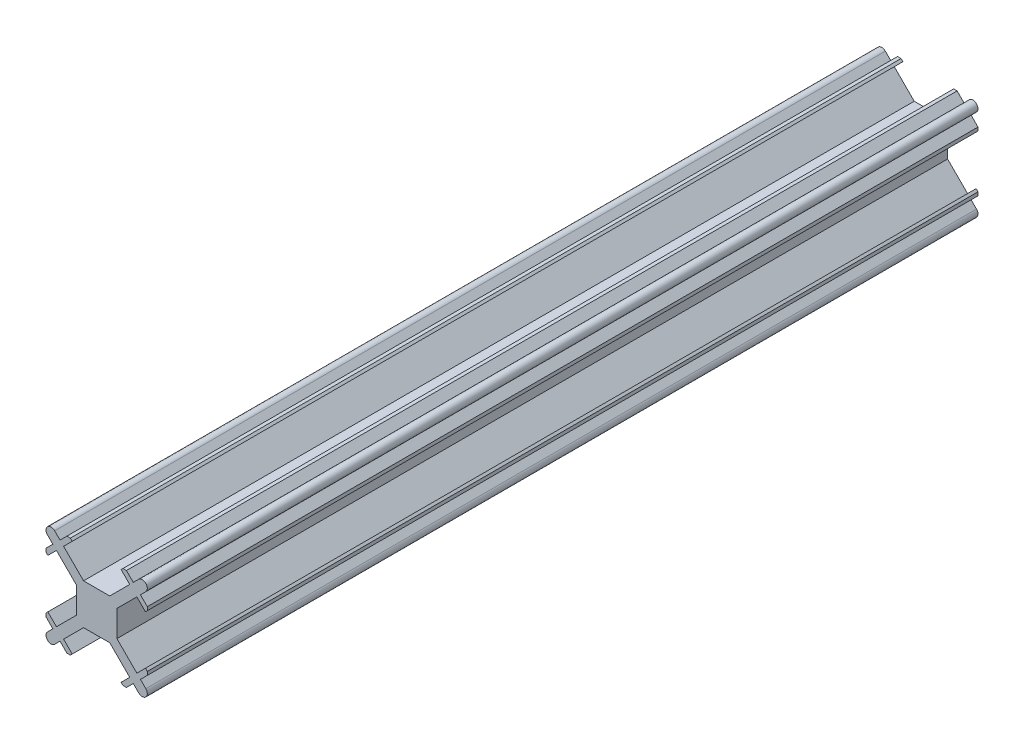
SolidWorks part; units mm, degrees
ref_plane "Front Plane" through (0, 0, 0) normal (0, 0, 1) x (1, 0, 0)
ref_plane "Top Plane" through (0, 0, 0) normal (0, 1, 0) x (1, 0, 0)
ref_plane "Right Plane" through (0, 0, 0) normal (1, 0, 0) x (0, 0, -1)
sketch "Sketch1" plane through (0, 0, 0) normal (0, 0, 1) x (1, 0, 0)
  line L0 (-5, -5) -> (5, 5) construction
  line L1 (-5, 5) -> (5, 5)
  line L2 (-5, 5) -> (-5, -5)
  line L3 (-5, -5) -> (5, -5)
  line L4 (5, 5) -> (5, -5)
  line L5 (-2, 2) -> (2, -2) construction
  line L6 (-2, 2) -> (2, 2)
  line L7 (-2, 2) -> (-2, -2)
  line L8 (-2, -2) -> (2, -2)
  line L9 (2, 2) -> (2, -2)
  dimension "D1" = 10
  dimension "D2" = 4
sketch "Sketch2" plane through (0, 0, 0) normal (0, 0, 1) x (1, 0, 0)
  line L0 (-4.8536, 4.1464) -> (-4.3232, 3.6161)
  line L1 (-4.1464, 4.8536) -> (-3.6161, 4.3232)
  line L2 (-4.5, 4.5) -> (-2, 2) construction
  line L3 (-5, 5) -> (5, 5) construction
  line L4 (-5, 5) -> (-5, -5) construction
  line L5 (-2.9393, 5) -> (-3.6161, 4.3232)
  line L6 (-5, 2.5958) -> (-4.8182, 2.414)
  line L7 (-4.8182, 2.414) -> (-3.9697, 3.2626)
  line L8 (-2.414, 4.8182) -> (-2.5958, 5)
  line L9 (-4.3232, 3.6161) -> (-5, 2.9393)
  line L10 (-3.2626, 3.9697) -> (-2.414, 4.8182)
  line L11 (-3.2626, 3.9697) -> (-1.2929, 2)
  line L12 (-3.9697, 3.2626) -> (-2, 1.2929)
  line L14 (-5, 2.9393) -> (-5, 2.5958)
  line L15 (-2.9393, 5) -> (-2.5958, 5)
  line L16 (-2, 2) -> (-2, -2) construction
  line L17 (-2, -2) -> (2, -2) construction
  line L18 (2, 2) -> (2, -2) construction
  line L19 (-2, 2) -> (2, 2) construction
  line L20 (-2, 1.2929) -> (-2, -1.2929)
  line L21 (-1.2929, -2) -> (1.2929, -2)
  line L22 (2, 1.2929) -> (2, -1.2929)
  line L23 (-1.2929, 2) -> (1.2929, 2)
  line L24 (4.1464, 4.8536) -> (3.6161, 4.3232)
  line L25 (4.8536, 4.1464) -> (4.3232, 3.6161)
  line L26 (5, 2.9393) -> (4.3232, 3.6161)
  line L27 (2.5958, 5) -> (2.414, 4.8182)
  line L28 (2.414, 4.8182) -> (3.2626, 3.9697)
  line L29 (4.8182, 2.414) -> (5, 2.5958)
  line L30 (3.6161, 4.3232) -> (2.9393, 5)
  line L31 (3.9697, 3.2626) -> (4.8182, 2.414)
  line L32 (3.9697, 3.2626) -> (2, 1.2929)
  line L33 (3.2626, 3.9697) -> (1.2929, 2)
  line L34 (2.9393, 5) -> (2.5958, 5)
  line L35 (5, 2.9393) -> (5, 2.5958)
  line L36 (4.8536, -4.1464) -> (4.3232, -3.6161)
  line L37 (4.1464, -4.8536) -> (3.6161, -4.3232)
  line L38 (2.9393, -5) -> (3.6161, -4.3232)
  line L39 (5, -2.5958) -> (4.8182, -2.414)
  line L40 (4.8182, -2.414) -> (3.9697, -3.2626)
  line L41 (2.414, -4.8182) -> (2.5958, -5)
  line L42 (4.3232, -3.6161) -> (5, -2.9393)
  line L43 (3.2626, -3.9697) -> (2.414, -4.8182)
  line L44 (3.2626, -3.9697) -> (1.2929, -2)
  line L45 (3.9697, -3.2626) -> (2, -1.2929)
  line L46 (5, -2.9393) -> (5, -2.5958)
  line L47 (2.9393, -5) -> (2.5958, -5)
  line L48 (-4.1464, -4.8536) -> (-3.6161, -4.3232)
  line L49 (-4.8536, -4.1464) -> (-4.3232, -3.6161)
  line L50 (-5, -2.9393) -> (-4.3232, -3.6161)
  line L51 (-2.5958, -5) -> (-2.414, -4.8182)
  line L52 (-2.414, -4.8182) -> (-3.2626, -3.9697)
  line L53 (-4.8182, -2.414) -> (-5, -2.5958)
  line L54 (-3.6161, -4.3232) -> (-2.9393, -5)
  line L55 (-3.9697, -3.2626) -> (-4.8182, -2.414)
  line L56 (-3.9697, -3.2626) -> (-2, -1.2929)
  line L57 (-3.2626, -3.9697) -> (-1.2929, -2)
  line L58 (-2.9393, -5) -> (-2.5958, -5)
  line L59 (-5, -2.9393) -> (-5, -2.5958)
  arc A0 (-4.8536, 4.1464) -> (-4.1464, 4.8536) centre (-4.5, 4.5) cw
  arc A1 (4.1464, 4.8536) -> (4.8536, 4.1464) centre (4.5, 4.5) cw
  arc A2 (4.8536, -4.1464) -> (4.1464, -4.8536) centre (4.5, -4.5) cw
  arc A3 (-4.1464, -4.8536) -> (-4.8536, -4.1464) centre (-4.5, -4.5) cw
  point P74 (0, 0)
  dimension "D3" = 1.25
  dimension "D1" = 1
  dimension "D2" = 3.4
  dimension "D4" = 0.5
  dimension "D5" = 4
extrude "Boss-Extrude1" add sketch "Sketch2" along normal mid plane 82
ref_plane "Plane1" through (0, 0, 0) normal (-1, 0, 0) x (0, 0, 1)
